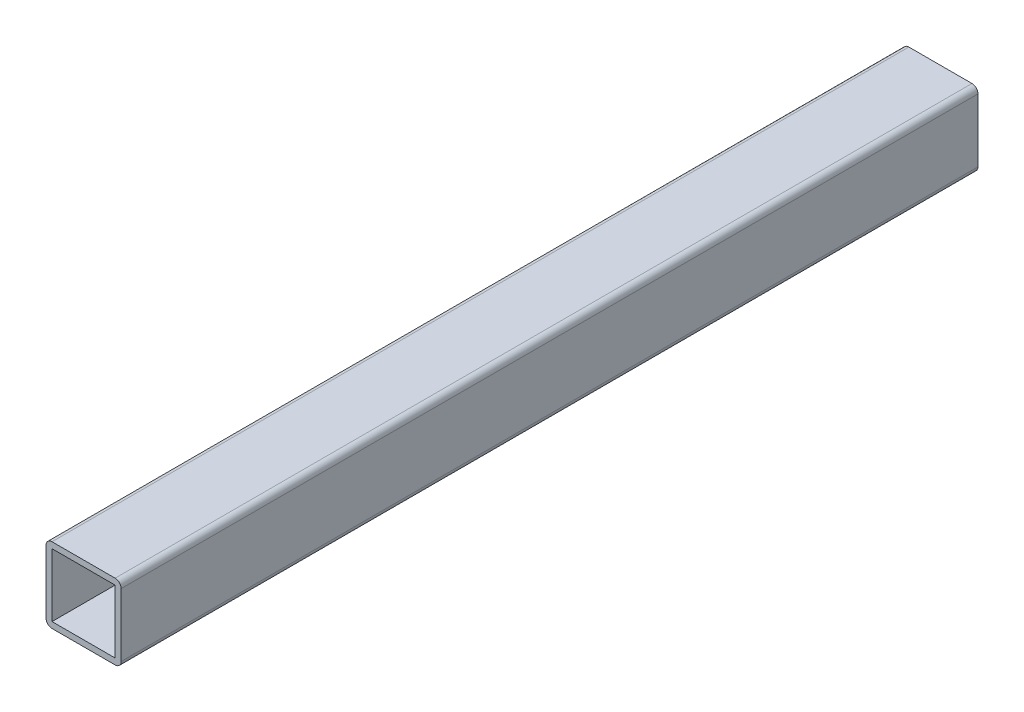
SolidWorks part; units mm, degrees
ref_plane "Спереди" through (0, 0, 0) normal (0, 0, 1) x (1, 0, 0)
ref_plane "Сверху" through (0, 0, 0) normal (0, 1, 0) x (1, 0, 0)
ref_plane "Справа" through (0, 0, 0) normal (1, 0, 0) x (0, 0, -1)
sketch "Эскиз1" plane through (0, 0, 0) normal (0, 0, 1) x (1, 0, 0)
  line L1 (4, 0) -> (46, 0)
  line L2 (0, 4) -> (0, 46)
  line L3 (4, 50) -> (46, 50)
  line L4 (50, 4) -> (50, 46)
  line L5 (4, 46) -> (46, 46)
  line L6 (4, 46) -> (4, 4)
  line L7 (4, 4) -> (46, 4)
  line L8 (46, 46) -> (46, 4)
  arc A0 (0, 46) -> (4, 50) centre (4, 46) cw
  arc A1 (4, 0) -> (0, 4) centre (4, 4) cw
  arc A2 (46, 0) -> (50, 4) centre (46, 4) ccw
  arc A3 (50, 46) -> (46, 50) centre (46, 46) ccw
  point P13 (0, 0)
  point P16 (50, 0)
  point P19 (50, 50)
  dimension "D7" = 4
  dimension "D1" = 50
  dimension "D2" = 50
  dimension "D3" = 4
  dimension "D4" = 4
  dimension "D5" = 4
  dimension "D6" = 4
extrude "Бобышка-Вытянуть1" add sketch "Эскиз1" along normal blind 570
